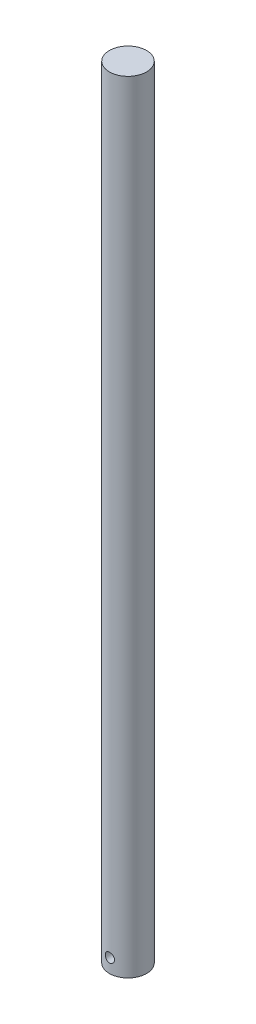
SolidWorks part; units mm, degrees
ref_plane "Front Plane" through (0, 0, 0) normal (0, 0, 1) x (1, 0, 0)
ref_plane "Top Plane" through (0, 0, 0) normal (0, 1, 0) x (1, 0, 0)
ref_plane "Right Plane" through (0, 0, 0) normal (1, 0, 0) x (0, 0, -1)
sketch "Sketch1" plane through (0, 0, 0) normal (0, 1, 0) x (1, 0, 0)
  circle A0 centre (0, 0) radius 10
extrude "Boss-Extrude1" add sketch "Sketch1" along normal blind 420
sketch "Sketch3" plane through (0, 0, 0) normal (0, 0, 1) x (1, 0, 0)
  line L0 (-27.7697, 7.45) -> (37.6226, 7.45) construction
  circle A0 centre (0, 7.45) radius 2.5
  dimension "D1" = 7.45
extrude "Cut-Extrude1" cut sketch "Sketch3" against normal mid plane 100
